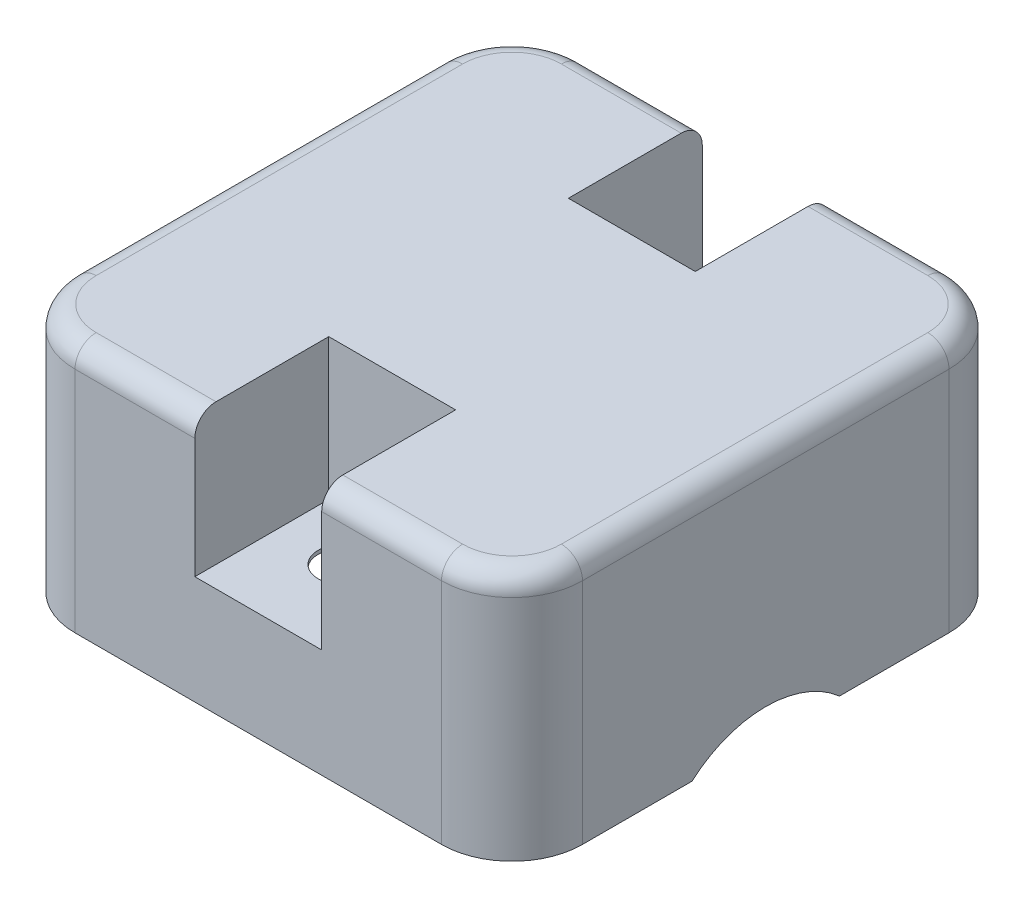
SolidWorks part; units mm, degrees
ref_plane "Front Plane" through (0, 0, 0) normal (0, 0, 1) x (1, 0, 0)
ref_plane "Top Plane" through (0, 0, 0) normal (0, 1, 0) x (1, 0, 0)
ref_plane "Right Plane" through (0, 0, 0) normal (1, 0, 0) x (0, 0, -1)
sketch "Sketch1" plane through (0, 0, 0) normal (0, 1, 0) x (1, 0, 0)
  line L0 (0, 0) -> (-30.25, 0)
  line L6 (0, 29.05) -> (0, 23.95)
  line L11 (-29.05, -29.05) -> (29.05, 29.05) construction
  line L12 (-29.05, 29.05) -> (29.05, -29.05) construction
  line L13 (0, -29.05) -> (0, -23.95)
  line L14 (-11, 18.85) -> (11, 18.85)
  line L15 (-11, 18.85) -> (-11, 29.05)
  line L17 (11, 18.85) -> (11, 29.05)
  line L18 (-11, 18.85) -> (11, 29.05) construction
  line L19 (-11, 29.05) -> (11, 18.85) construction
  line L21 (11, -18.85) -> (11, -29.05)
  line L22 (-11, -18.85) -> (11, -18.85)
  line L23 (-11, -18.85) -> (-11, -29.05)
  line L24 (0, 0) -> (36, 0)
  line L25 (0, 0) -> (0, 36.2117)
  line L26 (-26, 36.2117) -> (26, 36.2117)
  line L27 (36, 26.2117) -> (36, -26.2117)
  line L28 (-26, -36.2117) -> (26, -36.2117)
  line L29 (-36, 26.2117) -> (-36, -26.2117)
  line L30 (-11, 29.05) -> (-11, 36.2117)
  line L31 (11, 29.05) -> (11, 36.2117)
  line L32 (-11, -29.05) -> (-11, -36.2117)
  line L33 (11, -29.05) -> (11, -36.2117)
  line L34 (0, 0) -> (-34.87, 0)
  line L35 (0, 0) -> (0, -35.3717)
  line L36 (24.87, -35.3717) -> (-24.87, -35.3717)
  line L37 (-34.87, -25.3717) -> (-34.87, 25.3717)
  line L38 (24.87, 35.3717) -> (-24.87, 35.3717)
  line L39 (34.87, -25.3717) -> (34.87, 25.3717)
  circle A8 centre (0, 23.95) radius 3.5
  circle A9 centre (0, -23.95) radius 3.5
  arc A10 (26, 36.2117) -> (36, 26.2117) centre (26, 26.2117) cw
  arc A11 (26, -36.2117) -> (36, -26.2117) centre (26, -26.2117) ccw
  arc A12 (-26, -36.2117) -> (-36, -26.2117) centre (-26, -26.2117) cw
  arc A13 (-26, 36.2117) -> (-36, 26.2117) centre (-26, 26.2117) ccw
  arc A14 (-34.87, -25.3717) -> (-24.87, -35.3717) centre (-24.87, -25.3717) ccw
  arc A15 (-34.87, 25.3717) -> (-24.87, 35.3717) centre (-24.87, 25.3717) cw
  arc A16 (34.87, -25.3717) -> (24.87, -35.3717) centre (24.87, -25.3717) cw
  arc A17 (34.87, 25.3717) -> (24.87, 35.3717) centre (24.87, 25.3717) ccw
  point P4 (0, 0)
  point P10 (-30.25, -30.25)
  point P13 (-30.25, 30.25)
  point P32 (0, -36.2117)
  point P56 (0, 35.3717)
  dimension "D1" = 10
  dimension "D4" = 10
  dimension "D2" = 58.1
  dimension "D3" = 58.1
sketch "Sketch3" plane through (0, 0, 0) normal (0, 1, 0) x (1, 0, 0)
  line L0 (0, 0) -> (36, 0)
  line L1 (36, -26) -> (36, 26)
  line L2 (26, 36) -> (-26, 36)
  line L3 (0, 36) -> (0, 0)
  line L4 (26, -36) -> (-26, -36)
  line L5 (-36, -26) -> (-36, 26)
  line L6 (0, 0) -> (-35, 0)
  line L7 (0, 0) -> (0, -35)
  line L8 (-35, 25) -> (-35, -25)
  line L9 (-25, -35) -> (25, -35)
  line L10 (-25, 35) -> (25, 35)
  line L11 (35, 25) -> (35, -25)
  arc A0 (26, 36) -> (36, 26) centre (26, 26) cw
  arc A1 (26, -36) -> (36, -26) centre (26, -26) ccw
  arc A2 (-26, -36) -> (-36, -26) centre (-26, -26) cw
  arc A3 (-26, 36) -> (-36, 26) centre (-26, 26) ccw
  arc A4 (-25, -35) -> (-35, -25) centre (-25, -25) cw
  arc A5 (-25, 35) -> (-35, 25) centre (-25, 25) ccw
  arc A6 (25, -35) -> (35, -25) centre (25, -25) ccw
  arc A7 (25, 35) -> (35, 25) centre (25, 25) cw
  point P4 (0, 0)
  point P13 (0, -36)
  point P33 (0, 35)
  dimension "D1" = 10
  dimension "D2" = 10
extrude "Boss-Extrude1" add sketch "Sketch3" along normal blind 20 contours L11 A6 L9 A4 L8 A5 L10 A7 | L5 A3 L2 A0 L1 A1 L4 A2
ref_plane "Plane1" through (0, 20, 0) normal (0, 1, 0) x (1, 0, 0)
sketch "Sketch4" plane through (0, 20, 0) normal (0, 1, 0) x (1, 0, 0)
  line L0 (0, 0) -> (-36, 0)
  line L1 (-36, -26) -> (-36, 26) construction
  line L2 (0, 0) -> (0, 36)
  line L3 (26, 36) -> (-26, 36) construction
  line L4 (26, 36) -> (-26, 36)
  line L5 (-36, 26) -> (-36, -26)
  line L6 (26, -36) -> (-26, -36)
  line L7 (36, 26) -> (36, -26)
  arc A0 (-26, 36) -> (-36, 26) centre (-26, 26) ccw
  arc A1 (-26, -36) -> (-36, -26) centre (-26, -26) cw
  arc A2 (26, 36) -> (36, 26) centre (26, 26) cw
  arc A3 (26, -36) -> (36, -26) centre (26, -26) ccw
  point P21 (0, -36)
  dimension "D1" = 10
extrude "Boss-Extrude2" add sketch "Sketch4" along normal blind 2 contours L6 A3 L7 A2 L4 L2 L0 L5 A1 | L4 A0 L5 L0 L2
sketch "Sketch5" plane through (0, 22, 0) normal (0, 1, 0) x (1, 0, 0)
  line L0 (0, 0) -> (0, 24)
  line L1 (0, 36) -> (10, 36)
  line L2 (26, 36) -> (-26, 36) construction
  line L3 (10, 36) -> (10, 16)
  line L4 (10, 16) -> (-10, 16)
  line L5 (-10, 16) -> (-10, 36)
  line L6 (-10, 36) -> (10, 36)
  line L7 (0, 0) -> (19.3988, 0)
  line L8 (-10, -36) -> (10, -36)
  line L9 (-10, -16) -> (-10, -36)
  line L10 (10, -36) -> (10, -16)
  line L11 (10, -16) -> (-10, -16)
  circle A0 centre (0, 24) radius 3.5
  circle A1 centre (0, -24) radius 3.5
  point P4 (0, 0)
extrude "Boss-Extrude3" add sketch "Sketch5" against normal up to surface (22 mm away)
sketch "Sketch6" plane through (0, 22, 0) normal (0, 1, 0) x (1, 0, 0)
  line L0 (0, 0) -> (0, -17)
  line L1 (-9, -17) -> (9, -17)
  line L2 (9, -17) -> (9, -36)
  line L3 (-10, -36) -> (10, -36) construction
  line L4 (-9, -17) -> (-9, -36)
  line L5 (0, 0) -> (-13.4374, 0)
  line L6 (-9, 17) -> (-9, 36)
  line L7 (-9, 17) -> (9, 17)
  line L8 (9, 17) -> (9, 36)
  line L9 (-9, -36) -> (9, -36)
  line L10 (-9, 36) -> (9, 36)
  line M7 (-26, -36) -> (26, -36)
  line M11 (26, 36) -> (-26, 36)
extrude "Cut-Extrude1" cut sketch "Sketch6" against normal blind 20 contours L1 L4 L2 M7 | L7 L8 L6 M11
ref_plane "Plane2" through (0, 0, 0) normal (0, -1, 0) x (-1, 0, 0)
sketch "Sketch7" plane through (0, 0, 0) normal (0, -1, 0) x (-1, 0, 0)
  line L0 (-10, 35) -> (10, 35)
  line L1 (10, 35) -> (10, 16)
  line L2 (10, 16) -> (-10, 16)
  line L3 (-10, 16) -> (-10, 35)
  line L4 (0, 0) -> (15.7702, 0)
  line L5 (10, -16) -> (-10, -16)
  line L6 (10, -35) -> (10, -16)
  line L7 (-10, -35) -> (10, -35)
  line L8 (-10, -16) -> (-10, -35)
extrude "Cut-Extrude2" cut sketch "Sketch7" against normal blind 1.5 contours L3 L2 L1 L0 | L5 L8 L7 L6
fillet "Fillet1" radius 3 10 edges at (17.5, 22, 36) (17.5, 22, -36) (33.0711, 22, -33.0711) (36, 22, 0) (-17.5, 22, -36) (-33.0711, 22, -33.0711) (-17.5, 22, 36) (-33.0711, 22, 33.0711) (33.0711, 22, 33.0711) (-36, 22, 0)
sketch "Sketch8" plane through (36, 0, 0) normal (1, 0, 0) x (0, 0, -1)
  line L0 (0, 0) -> (0, 3)
  line L1 (0, 3) -> (0, -12.6)
  circle A0 centre (0, -12.6) radius 15.7
  point P4 (0, 3)
extrude "Cut-Extrude3" cut sketch "Sketch8" against normal blind 121.5
sketch "Sketch9" plane through (0, 0, 0) normal (0, -1, 0) x (-1, 0, 0)
  line L0 (25, 35) -> (-25, 35)
  line L1 (-10, 35) -> (10, 35) construction
  line L2 (-35, 25) -> (-35, -25)
  line L3 (-35, -9.3664) -> (-35, 9.3664) construction
  line L4 (26, 36) -> (-26, 36)
  line L5 (10, 36) -> (-10, 36) construction
  line L6 (-36, 26) -> (-36, -26)
  line L7 (-36, 9.3664) -> (-36, -9.3664) construction
  line L8 (-36, 0) -> (0, 0)
  line L9 (0, 0) -> (0, 36)
  line L10 (26, -36) -> (-26, -36)
  line L11 (25, -35) -> (-25, -35)
  line L12 (36, 26) -> (36, -26)
  line L13 (35, 25) -> (35, -25)
  arc A0 (-36, 26) -> (-26, 36) centre (-26, 26) cw
  arc A1 (-35, 25) -> (-25, 35) centre (-25, 25) cw
  arc A2 (-36, -26) -> (-26, -36) centre (-26, -26) ccw
  arc A3 (-35, -25) -> (-25, -35) centre (-25, -25) ccw
  arc A4 (35, 25) -> (25, 35) centre (25, 25) ccw
  arc A5 (36, 26) -> (26, 36) centre (26, 26) ccw
  arc A6 (35, -25) -> (25, -35) centre (25, -25) cw
  arc A7 (36, -26) -> (26, -36) centre (26, -26) cw
  point P25 (-35, 0)
  point P30 (0, 35)
  point P36 (0, -36)
  point P37 (0, -35)
  dimension "D1" = 10
extrude "Boss-Extrude6" add sketch "Sketch9" along normal blind 13.4 contours A6 L13 A4 L0 L9 L8 L2 A3 L11 | A1 L2 L8 L9 L0 | L6 A2 L10 A7 L12 A5 L4 A0
sketch "Sketch12" plane through (0, -13.4, 0) normal (0, -1, 0) x (1, 0, 0)
  line L0 (-36, -26) -> (-36, 26) construction
  line L1 (-36, 16.2339) -> (-35, 16.2339)
  line L2 (-36, 16.2339) -> (-36, -14.2476)
  line L3 (-36, -14.2476) -> (-35, -14.2476)
  line L4 (-35, 16.2339) -> (-35, -14.2476)
  line L5 (-35, -25) -> (-35, 25) construction
  line L6 (0, 0) -> (0, 35)
  line L7 (10, 35) -> (-10, 35) construction
  line L8 (36, -14.2476) -> (35, -14.2476)
  line L9 (36, 16.2339) -> (35, 16.2339)
  line L10 (36, 16.2339) -> (36, -14.2476)
  line L11 (35, 16.2339) -> (35, -14.2476)
extrude "Boss-Extrude7" add sketch "Sketch12" against normal blind 23.4 contours L2 L3 L4 L1 | L10 L8 L11 L9
sketch "Sketch13" plane through (-36, 0, 0) normal (-1, 0, 0) x (0, 0, 1)
  line L0 (0, -13.4) -> (0, -9.4607)
  line L1 (-26, -13.4) -> (26, -13.4) construction
  line L2 (0, -9.4607) -> (0, -25.3607)
  circle A0 centre (0, -25.3607) radius 15.9
  point P7 (0, -9.4607)
  point P9 (0, -25.3607)
  line M2 (-26, -13.4) -> (26, -13.4)
extrude "Cut-Extrude4" cut sketch "Sketch13" against normal blind 93.4 contours A0 L0 M2 | L0 A0 M2
